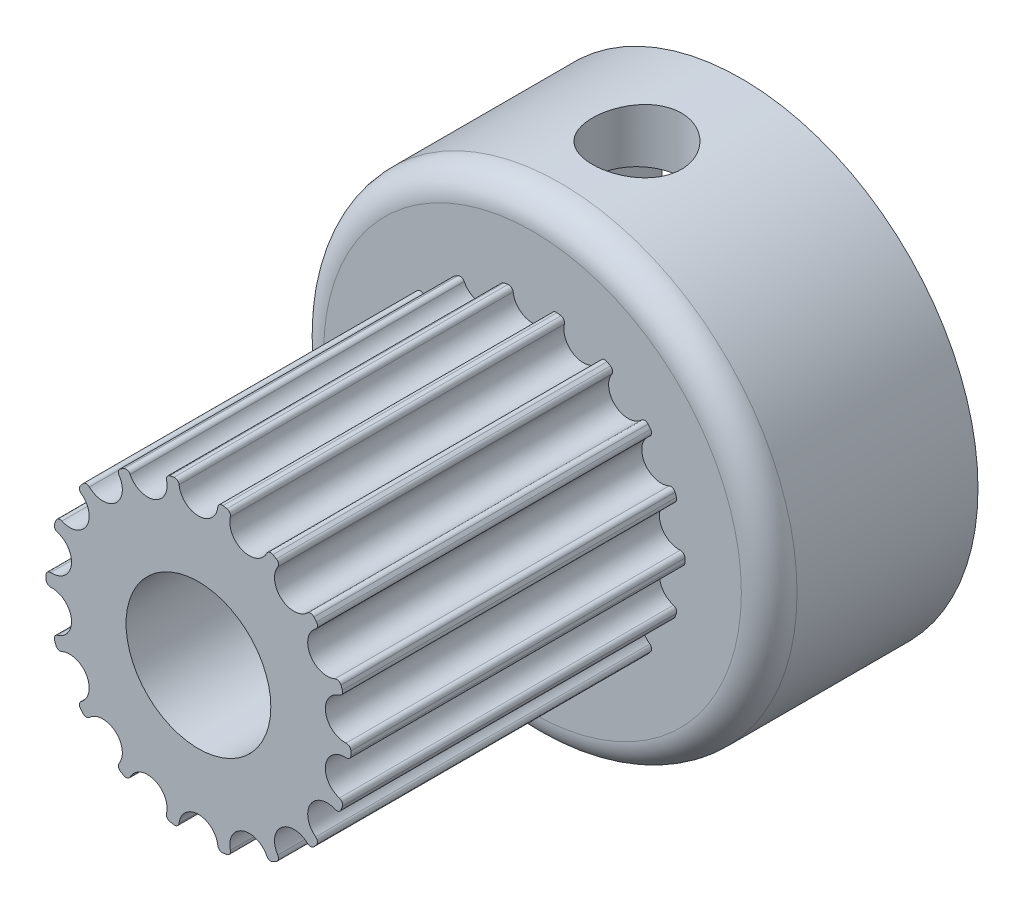
SolidWorks part; units mm, degrees
ref_plane "前视基准面" through (0, 0, 0) normal (0, 0, 1) x (1, 0, 0)
ref_plane "上视基准面" through (0, 0, 0) normal (0, 1, 0) x (1, 0, 0)
ref_plane "右视基准面" through (0, 0, 0) normal (1, 0, 0) x (0, 0, -1)
sketch "草图1" plane through (0, 0, 0) normal (0, 0, 1) x (1, 0, 0)
  circle A0 centre (0, 0) radius 8.5
  circle A1 centre (0, 0) radius 2.6
  dimension "D1" = 17
  dimension "D2" = 5.2
extrude "凸台-拉伸1" add sketch "草图1" along normal blind 7.5
fillet "圆角1" radius 1 1 edges at (8.5, 0, 7.5)
sketch "草图2" plane through (0, 0, 7.5) normal (0, 0, 1) x (1, 0, 0)
  circle A0 centre (0, 0) radius 2.6 construction
  circle A1 centre (0, 0) radius 2.6
  arc B0 (-0.8806, 5.4037) -> (-1.0207, 5.379) centre (0, 0) ccw
  arc B1 (-0.6958, 5.2633) -> (-0.8806, 5.4037) centre (-0.8548, 5.2458) ccw
  arc B2 (-0.6958, 5.2633) -> (0.6958, 5.2633) centre (0, 5.34) ccw
  arc B3 (-2.454, 4.7079) -> (-1.1463, 5.1839) centre (-1.8264, 5.018) ccw
  arc B4 (-1.0207, 5.379) -> (-1.1463, 5.1839) centre (-0.9909, 5.2218) ccw
  arc B5 (-3.9162, 3.5847) -> (-2.8502, 4.4792) centre (-3.4325, 4.0907) ccw
  arc B6 (-4.9061, 2.0291) -> (-4.2103, 3.2342) centre (-4.6246, 2.67) ccw
  arc B7 (-5.3042, 0.2287) -> (-5.0625, 1.5992) centre (-5.2589, 0.9273) ccw
  arc B8 (-5.0625, -1.5992) -> (-5.3042, -0.2287) centre (-5.2589, -0.9273) ccw
  arc B9 (-4.2103, -3.2342) -> (-4.9061, -2.0291) centre (-4.6246, -2.67) ccw
  arc B10 (-2.8502, -4.4792) -> (-3.9162, -3.5847) centre (-3.4325, -4.0907) ccw
  arc B11 (-1.1463, -5.1839) -> (-2.454, -4.7079) centre (-1.8264, -5.018) ccw
  arc B12 (0.6958, -5.2633) -> (-0.6958, -5.2633) centre (0, -5.34) ccw
  arc B13 (2.454, -4.7079) -> (1.1463, -5.1839) centre (1.8264, -5.018) ccw
  arc B14 (3.9162, -3.5847) -> (2.8502, -4.4792) centre (3.4325, -4.0907) ccw
  arc B15 (4.9061, -2.0291) -> (4.2103, -3.2342) centre (4.6246, -2.67) ccw
  arc B16 (5.3042, -0.2287) -> (5.0625, -1.5992) centre (5.2589, -0.9273) ccw
  arc B17 (5.0625, 1.5992) -> (5.3042, 0.2287) centre (5.2589, 0.9273) ccw
  arc B18 (4.2103, 3.2342) -> (4.9061, 2.0291) centre (4.6246, 2.67) ccw
  arc B19 (2.8502, 4.4792) -> (3.9162, 3.5847) centre (3.4325, 4.0907) ccw
  arc B20 (1.1463, 5.1839) -> (2.454, 4.7079) centre (1.8264, 5.018) ccw
  arc B21 (-2.6756, 4.7767) -> (-2.7989, 4.7055) centre (0, 0) ccw
  arc B22 (-2.454, 4.7079) -> (-2.6756, 4.7767) centre (-2.5974, 4.6371) ccw
  arc B23 (-2.7989, 4.7055) -> (-2.8502, 4.4792) centre (-2.7171, 4.568) ccw
  arc B24 (-4.148, 3.5735) -> (-4.2395, 3.4644) centre (0, 0) ccw
  arc B25 (-3.9162, 3.5847) -> (-4.148, 3.5735) centre (-4.0268, 3.4691) ccw
  arc B26 (-4.2395, 3.4644) -> (-4.2103, 3.2342) centre (-4.1156, 3.3632) ccw
  arc B27 (-5.12, 1.9393) -> (-5.1687, 1.8055) centre (0, 0) ccw
  arc B28 (-4.9061, 2.0291) -> (-5.12, 1.9393) centre (-4.9704, 1.8826) ccw
  arc B29 (-5.1687, 1.8055) -> (-5.0625, 1.5992) centre (-5.0177, 1.7528) ccw
  arc B30 (-5.4745, 0.0712) -> (-5.4745, -0.0712) centre (0, 0) ccw
  arc B31 (-5.3042, 0.2287) -> (-5.4745, 0.0712) centre (-5.3146, 0.0691) ccw
  arc B32 (-5.4745, -0.0712) -> (-5.3042, -0.2287) centre (-5.3146, -0.0691) ccw
  arc B33 (-5.1687, -1.8055) -> (-5.12, -1.9393) centre (0, 0) ccw
  arc B34 (-5.0625, -1.5992) -> (-5.1687, -1.8055) centre (-5.0177, -1.7528) ccw
  arc B35 (-5.12, -1.9393) -> (-4.9061, -2.0291) centre (-4.9704, -1.8826) ccw
  arc B36 (-4.2395, -3.4644) -> (-4.148, -3.5735) centre (0, 0) ccw
  arc B37 (-4.2103, -3.2342) -> (-4.2395, -3.4644) centre (-4.1156, -3.3632) ccw
  arc B38 (-4.148, -3.5735) -> (-3.9162, -3.5847) centre (-4.0268, -3.4691) ccw
  arc B39 (-2.7989, -4.7055) -> (-2.6756, -4.7767) centre (0, 0) ccw
  arc B40 (-2.8502, -4.4792) -> (-2.7989, -4.7055) centre (-2.7171, -4.568) ccw
  arc B41 (-2.6756, -4.7767) -> (-2.454, -4.7079) centre (-2.5974, -4.6371) ccw
  arc B42 (-1.0207, -5.379) -> (-0.8806, -5.4037) centre (0, 0) ccw
  arc B43 (-1.1463, -5.1839) -> (-1.0207, -5.379) centre (-0.9909, -5.2218) ccw
  arc B44 (-0.8806, -5.4037) -> (-0.6958, -5.2633) centre (-0.8548, -5.2458) ccw
  arc B45 (0.8806, -5.4037) -> (1.0207, -5.379) centre (0, 0) ccw
  arc B46 (0.6958, -5.2633) -> (0.8806, -5.4037) centre (0.8548, -5.2458) ccw
  arc B47 (1.0207, -5.379) -> (1.1463, -5.1839) centre (0.9909, -5.2218) ccw
  arc B48 (2.6756, -4.7767) -> (2.7989, -4.7055) centre (0, 0) ccw
  arc B49 (2.454, -4.7079) -> (2.6756, -4.7767) centre (2.5974, -4.6371) ccw
  arc B50 (2.7989, -4.7055) -> (2.8502, -4.4792) centre (2.7171, -4.568) ccw
  arc B51 (4.148, -3.5735) -> (4.2395, -3.4644) centre (0, 0) ccw
  arc B52 (3.9162, -3.5847) -> (4.148, -3.5735) centre (4.0268, -3.4691) ccw
  arc B53 (4.2395, -3.4644) -> (4.2103, -3.2342) centre (4.1156, -3.3632) ccw
  arc B54 (5.12, -1.9393) -> (5.1687, -1.8055) centre (0, 0) ccw
  arc B55 (4.9061, -2.0291) -> (5.12, -1.9393) centre (4.9704, -1.8826) ccw
  arc B56 (5.1687, -1.8055) -> (5.0625, -1.5992) centre (5.0177, -1.7528) ccw
  arc B57 (5.4745, -0.0712) -> (5.4745, 0.0712) centre (0, 0) ccw
  arc B58 (5.3042, -0.2287) -> (5.4745, -0.0712) centre (5.3146, -0.0691) ccw
  arc B59 (5.4745, 0.0712) -> (5.3042, 0.2287) centre (5.3146, 0.0691) ccw
  arc B60 (5.1687, 1.8055) -> (5.12, 1.9393) centre (0, 0) ccw
  arc B61 (5.0625, 1.5992) -> (5.1687, 1.8055) centre (5.0177, 1.7528) ccw
  arc B62 (5.12, 1.9393) -> (4.9061, 2.0291) centre (4.9704, 1.8826) ccw
  arc B63 (4.2395, 3.4644) -> (4.148, 3.5735) centre (0, 0) ccw
  arc B64 (4.2103, 3.2342) -> (4.2395, 3.4644) centre (4.1156, 3.3632) ccw
  arc B65 (4.148, 3.5735) -> (3.9162, 3.5847) centre (4.0268, 3.4691) ccw
  arc B66 (2.7989, 4.7055) -> (2.6756, 4.7767) centre (0, 0) ccw
  arc B67 (2.8502, 4.4792) -> (2.7989, 4.7055) centre (2.7171, 4.568) ccw
  arc B68 (2.6756, 4.7767) -> (2.454, 4.7079) centre (2.5974, 4.6371) ccw
  arc B69 (1.0207, 5.379) -> (0.8806, 5.4037) centre (0, 0) ccw
  arc B70 (1.1463, 5.1839) -> (1.0207, 5.379) centre (0.9909, 5.2218) ccw
  arc B71 (0.8806, 5.4037) -> (0.6958, 5.2633) centre (0.8548, 5.2458) ccw
sketch_block_instance "GT2 18齿-1"
sketch_block "GT2 18齿"
extrude "凸台-拉伸2" add sketch "草图2" along normal blind 12
sketch "草图4" plane through (0, 0, 0) normal (0, 1, 0) x (1, 0, 0)
  line L0 (8.5, 0) -> (-8.5, 0) construction
  circle A0 centre (0, -3.75) radius 1.6
  dimension "D1" = 3.2
  dimension "D2" = 3.75
extrude "切除-拉伸1" cut sketch "草图4" against normal through all and the other way through all
sketch "草图5" plane through (0, 0, 0) normal (0, 0, -1) x (-1, 0, 0)
  line L0 (0, 0) -> (0, 9.103) construction
  line L1 (-2.85, 6.5) -> (2.85, 6.5)
  line L2 (-2.85, 6.5) -> (-2.85, 3.8)
  line L3 (-2.85, 3.8) -> (2.85, 3.8)
  line L4 (2.85, 6.5) -> (2.85, 3.8)
  dimension "D1" = 3.8
  dimension "D2" = 2.7
  dimension "D3" = 5.7
extrude "切除-拉伸2" cut sketch "草图5" against normal blind 7.05
mirror "镜向1" about plane through (0, 0, 0) normal (0, 1, 0) of "切除-拉伸2", "切除-拉伸1"
